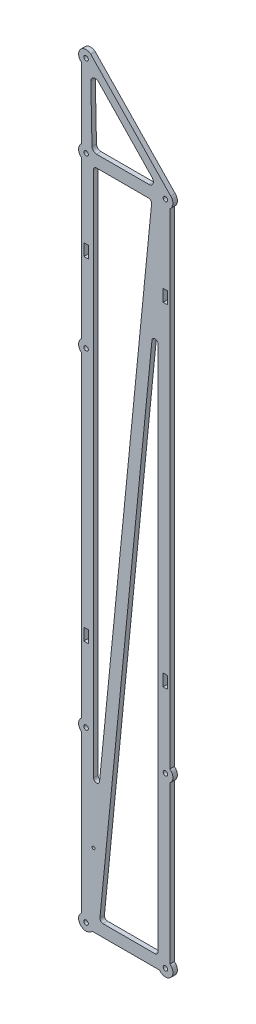
SolidWorks part; units mm, degrees
ref_plane "前视基准面" through (0, 0, 0) normal (0, 0, 1) x (1, 0, 0)
ref_plane "上视基准面" through (0, 0, 0) normal (0, 1, 0) x (1, 0, 0)
ref_plane "右视基准面" through (0, 0, 0) normal (1, 0, 0) x (0, 0, -1)
sketch "草图1" plane through (0, 0, 0) normal (0, 0, 1) x (1, 0, 0)
  line L8 (0, -445) -> (0, -112.82) construction
  line L12 (-3, -4) -> (-3, -328.18) construction
  line L13 (-3, -336.18) -> (-3, -441) construction
  line L20 (0, 0) -> (53, 0) construction
  line L21 (26.5, 0) -> (26.5, -16.3301) construction
  line L22 (53, -445) -> (53, -332.18) construction
  line L27 (56, -448) -> (56, 3) construction
  line L29 (53, -445) -> (53, 0) construction
  line L34 (56, -336.18) -> (56, -441)
  line L35 (56, -4) -> (56, -328.18)
  line L36 (6.9382, 3) -> (41.9698, 3)
  line L37 (4, -448) -> (49, -448)
  line L38 (0, -445) -> (5, -445) construction
  line L39 (5, -445) -> (5, -440) construction
  line L40 (53, -5) -> (48, -5) construction
  line L41 (5, -440) -> (48, -5) construction
  line L42 (48, -5) -> (5, -5) construction
  line L44 (5, -440) -> (48, -440) construction
  line L45 (48, -440) -> (48, -5) construction
  line L46 (8.9806, -440.3935) -> (51.9806, -5.3935) construction
  line L47 (48, -86.2261) -> (48, -438)
  line L48 (11.2269, -440) -> (46, -440)
  line L49 (9.2366, -437.8033) -> (44.0097, -86.0293)
  line L50 (1.0194, -439.6065) -> (44.0194, -4.6065) construction
  line L51 (43.7634, -7.1967) -> (8.9903, -358.9707)
  line L53 (7, -5) -> (41.7731, -5)
  line L54 (-3, -438.8329) -> (-3, -429.0179)
  line L67 (0, -112.82) -> (0, 0) construction
  line L69 (-3, -108.82) -> (-3, -4)
  line L70 (-3, -429.0179) -> (-3, -336.18)
  line L72 (-3, -438.8329) -> (-3, -441)
  line L75 (-3, -116.82) -> (-3, -328.18)
  line L76 (5, -358.7739) -> (5, -7)
  line L77 (54.52, -52.39) -> (54.52, -60.43)
  line L78 (-1.52, -52.39) -> (1.52, -52.39)
  line L79 (0, 0) -> (0, 55) construction
  line L80 (-3, 4) -> (-3, 51)
  line L81 (3.9388, 5.9375) -> (3.1603, 43.3046)
  line L82 (8.3256, 45.4428) -> (44.1358, 8.0757)
  line L83 (3, 59) -> (56.5355, 3.5355)
  line L84 (-1.52, -52.39) -> (-1.52, -60.43)
  line L85 (-1.52, -60.43) -> (1.52, -60.43)
  line L86 (1.52, -52.39) -> (1.52, -60.43)
  line L87 (51.48, -274.89) -> (51.48, -282.93)
  line L88 (-1.52, -274.89) -> (1.52, -274.89)
  line L89 (51.48, -52.39) -> (51.48, -60.43)
  line L90 (54.52, -52.39) -> (51.48, -52.39)
  line L91 (54.52, -60.43) -> (51.48, -60.43)
  line L92 (-1.52, -274.89) -> (-1.52, -282.93)
  line L93 (-1.52, -282.93) -> (1.52, -282.93)
  line L94 (1.52, -274.89) -> (1.52, -282.93)
  line L97 (54.52, -274.89) -> (54.52, -282.93)
  line L98 (54.52, -274.89) -> (51.48, -274.89)
  line L99 (54.52, -282.93) -> (51.48, -282.93)
  circle A0 centre (0, 0) radius 1.5
  circle A3 centre (0, -445) radius 1.5
  circle A4 centre (0, -332.18) radius 1.5
  circle A6 centre (0, 0) radius 5 construction
  arc A12 (4, -448) -> (-3, -441) centre (0, -445) cw
  arc A17 (-3, -336.18) -> (-3, -328.18) centre (0, -332.18) cw
  circle A24 centre (53, -332.18) radius 5 construction
  circle A25 centre (53, -445) radius 5 construction
  circle A26 centre (53, 0) radius 5 construction
  arc A27 (56, -336.18) -> (56, -328.18) centre (53, -332.18) ccw
  arc A29 (49, -448) -> (56, -441) centre (53, -445) ccw
  circle A30 centre (53, -332.18) radius 1.5
  circle A31 centre (53, -445) radius 1.5
  circle A32 centre (53, 0) radius 1.5
  arc A33 (48, -438) -> (46, -440) centre (46, -438) cw
  arc A34 (11.2269, -440) -> (9.2366, -437.8033) centre (11.2269, -438) cw
  arc A35 (48, -86.2261) -> (44.0097, -86.0293) centre (46, -86.2261) ccw
  arc A36 (43.7634, -7.1967) -> (41.7731, -5) centre (41.7731, -7) ccw
  arc A37 (7, -5) -> (5, -7) centre (7, -7) ccw
  arc A38 (8.9903, -358.9707) -> (5, -358.7739) centre (7, -358.7739) cw
  circle A39 centre (5, -399.3377) radius 1
  circle A52 centre (0, 55) radius 1.5
  circle A53 centre (0, 55) radius 5 construction
  arc A54 (56.5355, 3.5355) -> (56, -4) centre (53, 0) cw
  arc A55 (-3, 51) -> (3, 59) centre (0, 55) cw
  arc A56 (-3, -4) -> (-3, 4) centre (0, 0) cw
  arc A58 (8.3256, 45.4428) -> (3.1603, 43.3046) centre (6.1597, 43.3671) ccw
  arc A59 (44.1358, 8.0757) -> (41.9698, 3) centre (41.9698, 6) cw
  arc A60 (6.9382, 3) -> (3.9388, 5.9375) centre (6.9382, 6) cw
  circle A61 centre (0, -112.82) radius 1.5
  circle A62 centre (0, -112.82) radius 5 construction
  arc A63 (-3, -116.82) -> (-3, -108.82) centre (0, -112.82) cw
  point P22 (0, -278.91)
  point P59 (9.0195, -440)
  point P62 (48, -45.6623)
  point P65 (43.9805, -5)
  point P71 (5, -399.3377)
  point P77 (0, -56.41)
  point P106 (-3, -435.3688)
  point P110 (-3, -430.75)
  point P128 (3, 51)
  point P131 (49, 3)
  point P134 (4, 3)
  dimension "D2" = 53
  dimension "D3" = 2
  dimension "D8" = 3
extrude "凸台-拉伸1" add sketch "草图1" along normal blind 3
